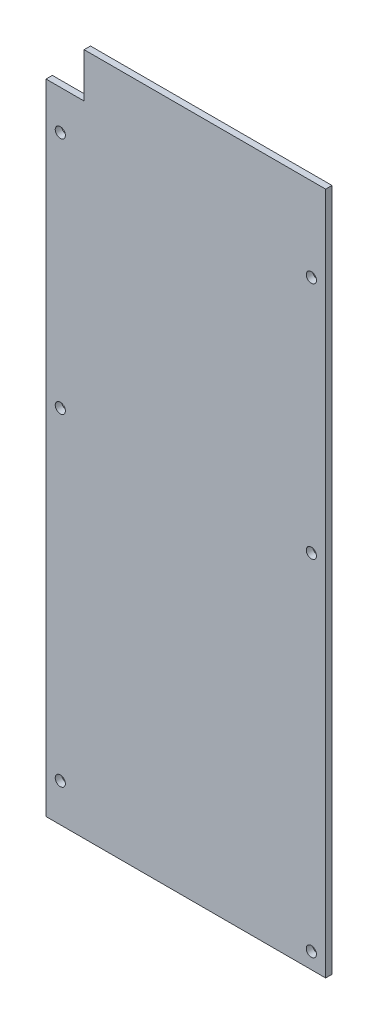
SolidWorks part; units mm, degrees
ref_plane "Front Plane" through (0, 0, 0) normal (0, 0, 1) x (1, 0, 0)
ref_plane "Top Plane" through (0, 0, 0) normal (0, 1, 0) x (1, 0, 0)
ref_plane "Right Plane" through (0, 0, 0) normal (1, 0, 0) x (0, 0, -1)
sketch "Sketch1" plane through (0, 0, 0) normal (0, 0, 1) x (1, 0, 0)
  line L0 (44, 0) -> (44, 91.5257) construction
  line L1 (0, 0) -> (88, 0)
  line L2 (0, 0) -> (0, 215)
  line L3 (0, 215) -> (88, 215)
  line L4 (88, 0) -> (88, 215)
  line L5 (0, 215) -> (12, 215)
  line L6 (0, 215) -> (0, 201)
  line L7 (0, 201) -> (12, 201)
  line L8 (12, 215) -> (12, 201)
  circle A0 centre (4.5, 12) radius 1.6
  circle A1 centre (4.5, 113.59) radius 1.6
  circle A3 centre (4.5, 188.68) radius 1.6
  circle A4 centre (83.5, 188.68) radius 1.6
  circle A6 centre (83.5, 113.59) radius 1.6
  circle A8 centre (83.5, 5) radius 1.6
  dimension "D6" = 3.2
  dimension "D1" = 215
  dimension "D2" = 88
  dimension "D3" = 14
  dimension "D4" = 12
  dimension "D5" = 4.5
  dimension "D7" = 12
  dimension "D8" = 113.59
  dimension "D9" = 5
  dimension "D10" = 188.68
  dimension "D11" = 4.5
extrude "Boss-Extrude1" add sketch "Sketch1" along normal blind 2
